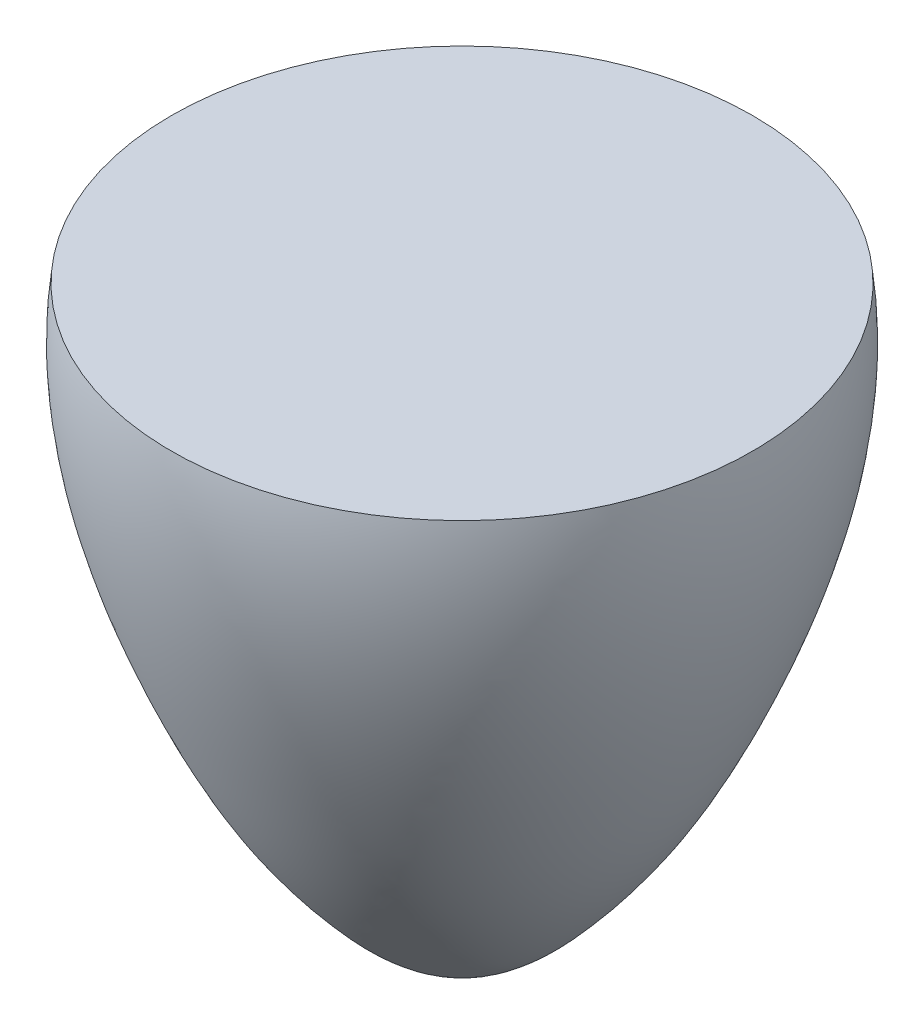
SolidWorks part; units mm, degrees
ref_plane "Front Plane" through (0, 0, 0) normal (0, 0, 1) x (1, 0, 0)
ref_plane "Top Plane" through (0, 0, 0) normal (0, 1, 0) x (1, 0, 0)
ref_plane "Right Plane" through (0, 0, 0) normal (1, 0, 0) x (0, 0, -1)
sketch "Sketch1" plane through (0, 0, 0) normal (0, 0, 1) x (1, 0, 0)
  line L0 (0, 6.419) -> (0, 38.1352) construction
  line L1 (0, 0) -> (0, 20.4)
  line L2 (0, 20.4) -> (-10.1851, 20.4)
  spline S0 degree 3 poles (0, 0) (-1.7382, 0.2144) (-3.814, 2.1708) (-6.3141, 5.5748) (-8.0789, 9.2076) (-9.917, 14.1533) (-10.4948, 17.99) (-10.1851, 20.4) knots 0 0 0 0 0.202199 0.344789 0.5249 0.701476 1 1 1 1
revolve "Revolve1" add sketch "Sketch1" angle 360 about L0
